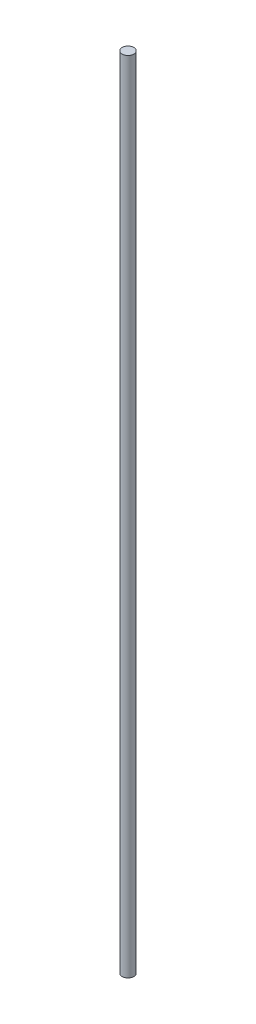
SolidWorks part; units mm, degrees
ref_plane "Alzado" through (0, 0, 0) normal (0, 0, 1) x (1, 0, 0)
ref_plane "Planta" through (0, 0, 0) normal (0, 1, 0) x (1, 0, 0)
ref_plane "Vista lateral" through (0, 0, 0) normal (1, 0, 0) x (0, 0, -1)
sketch "Croquis1" plane through (0, 0, 0) normal (0, 1, 0) x (1, 0, 0)
  circle A0 centre (0, 0) radius 4
  dimension "D1" = 8
extrude "Saliente-Extruir1" add sketch "Croquis1" along normal blind 550
